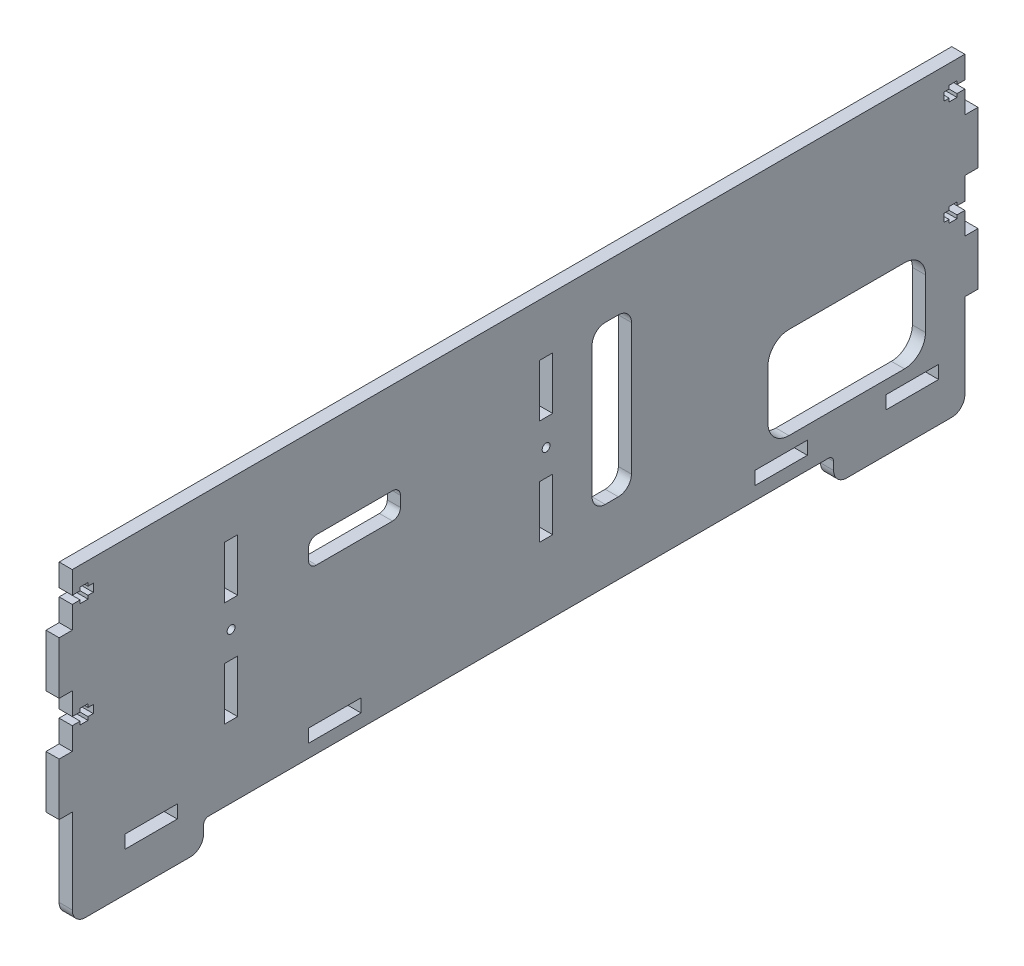
SolidWorks part; units mm, degrees
ref_plane "前视基准面" through (0, 0, 0) normal (0, 0, 1) x (1, 0, 0)
ref_plane "上视基准面" through (0, 0, 0) normal (0, 1, 0) x (1, 0, 0)
ref_plane "右视基准面" through (0, 0, 0) normal (1, 0, 0) x (0, 0, -1)
sketch "草图1" plane through (0, 0, 0) normal (1, 0, 0) x (0, 0, -1)
  line L0 (-75.7709, -36.3237) -> (-75.7709, -33.3237)
  line L1 (-125.7709, 75.9763) -> (214.2291, 75.9763)
  line L2 (-125.7709, 75.9763) -> (-125.7709, 67.4763)
  line L3 (-120.7709, -41.3237) -> (-80.7709, -41.3237)
  line L4 (214.2291, 75.9763) -> (214.2291, 67.4763)
  line L5 (-73.7709, -31.3237) -> (162.2291, -31.3237)
  line L6 (164.2291, -33.3237) -> (164.2291, -36.3237)
  line L7 (-130.7709, 83.5386) -> (-130.7709, -56.3914) construction
  line L8 (219.2291, -54.2304) -> (219.2291, 91.1431) construction
  line L9 (-125.7709, 35.9763) -> (-125.7709, 27.4763)
  line L10 (-130.7709, 55.9763) -> (-125.7709, 55.9763)
  line L11 (-130.7709, 55.9763) -> (-130.7709, 35.9763)
  line L12 (-130.7709, 35.9763) -> (-125.7709, 35.9763)
  line L13 (-125.7709, -4.0237) -> (-125.7709, -36.3237)
  line L14 (-130.7709, 15.9763) -> (-125.7709, 15.9763)
  line L15 (-130.7709, 15.9763) -> (-130.7709, -4.0237)
  line L16 (-130.7709, -4.0237) -> (-125.7709, -4.0237)
  line L17 (214.2291, 35.9763) -> (214.2291, 27.4763)
  line L18 (214.2291, 55.9763) -> (219.2291, 55.9763)
  line L19 (214.2291, -4.0237) -> (214.2291, -36.3237)
  line L20 (214.2291, 35.9763) -> (219.2291, 35.9763)
  line L21 (219.2291, 55.9763) -> (219.2291, 35.9763)
  line L22 (214.2291, 15.9763) -> (219.2291, 15.9763)
  line L23 (169.2291, -41.3237) -> (209.2291, -41.3237)
  line L24 (214.2291, -4.0237) -> (219.2291, -4.0237)
  line L25 (219.2291, 15.9763) -> (219.2291, -4.0237)
  line L26 (-67.7709, 106.6137) -> (-67.7709, -95.6066) construction
  line L27 (57.2291, 100.1396) -> (57.2291, -68.1869) construction
  line L28 (-105.7709, 93.1876) -> (-105.7709, -75.8237) construction
  line L29 (57.2291, 55.9763) -> (52.2291, 55.9763)
  line L30 (57.2291, 55.9763) -> (57.2291, 35.9763)
  line L31 (57.2291, 35.9763) -> (52.2291, 35.9763)
  line L32 (52.2291, 55.9763) -> (52.2291, 35.9763)
  line L33 (57.2291, 15.9763) -> (52.2291, 15.9763)
  line L34 (57.2291, 15.9763) -> (57.2291, -4.0237)
  line L35 (57.2291, -4.0237) -> (52.2291, -4.0237)
  line L36 (52.2291, 15.9763) -> (52.2291, -4.0237)
  line L37 (-67.7709, 55.9763) -> (-62.7709, 55.9763)
  line L38 (-67.7709, 55.9763) -> (-67.7709, 35.9763)
  line L39 (-67.7709, 35.9763) -> (-62.7709, 35.9763)
  line L40 (-62.7709, 55.9763) -> (-62.7709, 35.9763)
  line L41 (-67.7709, 15.9763) -> (-62.7709, 15.9763)
  line L42 (-67.7709, 15.9763) -> (-67.7709, -4.0237)
  line L43 (-67.7709, -4.0237) -> (-62.7709, -4.0237)
  line L44 (-62.7709, 15.9763) -> (-62.7709, -4.0237)
  line L45 (-15.7709, 93.1876) -> (-15.7709, -75.8237) construction
  line L46 (-15.7709, -26.3237) -> (255.6301, -26.3237) construction
  line L47 (-15.7709, -21.3237) -> (-35.7709, -21.3237)
  line L48 (-15.7709, -21.3237) -> (-15.7709, -26.3237)
  line L49 (-15.7709, -26.3237) -> (-35.7709, -26.3237)
  line L50 (-35.7709, -21.3237) -> (-35.7709, -26.3237)
  line L51 (-85.7709, -21.3237) -> (-105.7709, -21.3237)
  line L52 (-85.7709, -21.3237) -> (-85.7709, -26.3237)
  line L53 (-85.7709, -26.3237) -> (-105.7709, -26.3237)
  line L54 (-105.7709, -21.3237) -> (-105.7709, -26.3237)
  line L55 (204.2291, 86.5162) -> (204.2291, -54.2304) construction
  line L56 (214.2291, 67.4763) -> (211.2291, 67.4763)
  line L57 (204.2291, -26.3237) -> (184.2291, -26.3237)
  line L58 (204.2291, -26.3237) -> (204.2291, -21.3237)
  line L59 (204.2291, -21.3237) -> (184.2291, -21.3237)
  line L60 (184.2291, -26.3237) -> (184.2291, -21.3237)
  line L61 (154.2291, -26.3237) -> (134.2291, -26.3237)
  line L62 (154.2291, -26.3237) -> (154.2291, -21.3237)
  line L63 (154.2291, -21.3237) -> (134.2291, -21.3237)
  line L64 (134.2291, -26.3237) -> (134.2291, -21.3237)
  line L65 (191.2291, 18.6763) -> (147.2291, 18.6763)
  line L66 (199.2291, 10.6763) -> (199.2291, -8.3237)
  line L67 (191.2291, -16.3237) -> (147.2291, -16.3237)
  line L68 (139.2291, 10.6763) -> (139.2291, -8.3237)
  line L69 (82.2291, 55.9763) -> (77.2291, 55.9763)
  line L70 (87.2291, 50.9763) -> (87.2291, 0.9763)
  line L71 (82.2291, -4.0237) -> (77.2291, -4.0237)
  line L72 (72.2291, 50.9763) -> (72.2291, 0.9763)
  line L73 (-32.7709, 40.9763) -> (-3.7709, 40.9763)
  line L74 (-35.7709, 37.9763) -> (-35.7709, 33.9763)
  line L75 (-32.7709, 30.9763) -> (-3.7709, 30.9763)
  line L76 (-0.7709, 37.9763) -> (-0.7709, 33.9763)
  line L77 (206.2291, 67.4763) -> (206.2291, 64.4763)
  line L78 (206.2291, 64.4763) -> (208.2291, 64.4763)
  line L79 (211.2291, 64.4763) -> (211.2291, 63.2263)
  line L80 (211.2291, 68.7263) -> (208.2291, 68.7263)
  line L81 (211.2291, 68.7263) -> (211.2291, 67.4763)
  line L82 (211.2291, 63.2263) -> (208.2291, 63.2263)
  line L83 (208.2291, 68.7263) -> (208.2291, 67.4763)
  line L84 (208.2291, 67.4763) -> (206.2291, 67.4763)
  line L85 (208.2291, 64.4763) -> (208.2291, 63.2263)
  line L86 (211.2291, 64.4763) -> (214.2291, 64.4763)
  line L87 (214.2291, 64.4763) -> (214.2291, 55.9763)
  line L88 (-125.7709, 67.4763) -> (-122.7709, 67.4763)
  line L89 (-122.7709, 67.4763) -> (-122.7709, 68.7263)
  line L90 (-122.7709, 68.7263) -> (-119.7709, 68.7263)
  line L91 (-119.7709, 68.7263) -> (-119.7709, 67.4763)
  line L92 (-119.7709, 67.4763) -> (-117.7709, 67.4763)
  line L93 (-117.7709, 67.4763) -> (-117.7709, 64.4763)
  line L94 (-117.7709, 64.4763) -> (-119.7709, 64.4763)
  line L95 (-119.7709, 64.4763) -> (-119.7709, 63.2263)
  line L96 (-119.7709, 63.2263) -> (-122.7709, 63.2263)
  line L97 (-122.7709, 63.2263) -> (-122.7709, 64.4763)
  line L98 (-122.7709, 64.4763) -> (-125.7709, 64.4763)
  line L99 (214.2291, 27.4763) -> (211.2291, 27.4763)
  line L100 (206.2291, 27.4763) -> (206.2291, 24.4763)
  line L101 (206.2291, 24.4763) -> (208.2291, 24.4763)
  line L102 (211.2291, 24.4763) -> (211.2291, 23.2263)
  line L103 (211.2291, 28.7263) -> (208.2291, 28.7263)
  line L104 (211.2291, 28.7263) -> (211.2291, 27.4763)
  line L105 (211.2291, 23.2263) -> (208.2291, 23.2263)
  line L106 (208.2291, 28.7263) -> (208.2291, 27.4763)
  line L107 (208.2291, 27.4763) -> (206.2291, 27.4763)
  line L108 (208.2291, 24.4763) -> (208.2291, 23.2263)
  line L109 (211.2291, 24.4763) -> (214.2291, 24.4763)
  line L110 (214.2291, 24.4763) -> (214.2291, 15.9763)
  line L111 (-125.7709, 27.4763) -> (-122.7709, 27.4763)
  line L112 (-122.7709, 27.4763) -> (-122.7709, 28.7263)
  line L113 (-122.7709, 28.7263) -> (-119.7709, 28.7263)
  line L114 (-119.7709, 28.7263) -> (-119.7709, 27.4763)
  line L115 (-119.7709, 27.4763) -> (-117.7709, 27.4763)
  line L116 (-117.7709, 27.4763) -> (-117.7709, 24.4763)
  line L117 (-117.7709, 24.4763) -> (-119.7709, 24.4763)
  line L118 (-119.7709, 24.4763) -> (-119.7709, 23.2263)
  line L119 (-119.7709, 23.2263) -> (-122.7709, 23.2263)
  line L120 (-122.7709, 23.2263) -> (-122.7709, 24.4763)
  line L121 (-122.7709, 24.4763) -> (-125.7709, 24.4763)
  line L122 (-125.7709, 64.4763) -> (-125.7709, 55.9763)
  line L123 (-125.7709, 24.4763) -> (-125.7709, 15.9763)
  arc A0 (209.2291, -41.3237) -> (214.2291, -36.3237) centre (209.2291, -36.3237) ccw
  arc A1 (164.2291, -36.3237) -> (169.2291, -41.3237) centre (169.2291, -36.3237) ccw
  arc A2 (-75.7709, -36.3237) -> (-80.7709, -41.3237) centre (-80.7709, -36.3237) cw
  arc A3 (-125.7709, -36.3237) -> (-120.7709, -41.3237) centre (-120.7709, -36.3237) ccw
  arc A4 (162.2291, -31.3237) -> (164.2291, -33.3237) centre (162.2291, -33.3237) cw
  arc A5 (-75.7709, -33.3237) -> (-73.7709, -31.3237) centre (-73.7709, -33.3237) cw
  arc A6 (147.2291, 18.6763) -> (139.2291, 10.6763) centre (147.2291, 10.6763) ccw
  arc A7 (147.2291, -16.3237) -> (139.2291, -8.3237) centre (147.2291, -8.3237) cw
  arc A8 (199.2291, -8.3237) -> (191.2291, -16.3237) centre (191.2291, -8.3237) cw
  arc A9 (191.2291, 18.6763) -> (199.2291, 10.6763) centre (191.2291, 10.6763) cw
  arc A10 (87.2291, 0.9763) -> (82.2291, -4.0237) centre (82.2291, 0.9763) cw
  arc A11 (77.2291, -4.0237) -> (72.2291, 0.9763) centre (77.2291, 0.9763) cw
  arc A12 (77.2291, 55.9763) -> (72.2291, 50.9763) centre (77.2291, 50.9763) ccw
  arc A13 (82.2291, 55.9763) -> (87.2291, 50.9763) centre (82.2291, 50.9763) cw
  arc A14 (-32.7709, 40.9763) -> (-35.7709, 37.9763) centre (-32.7709, 37.9763) ccw
  arc A15 (-35.7709, 33.9763) -> (-32.7709, 30.9763) centre (-32.7709, 33.9763) ccw
  arc A16 (-3.7709, 30.9763) -> (-0.7709, 33.9763) centre (-3.7709, 33.9763) ccw
  arc A17 (-3.7709, 40.9763) -> (-0.7709, 37.9763) centre (-3.7709, 37.9763) cw
  circle A18 centre (54.7291, 25.9763) radius 1.5
  circle A19 centre (-65.2709, 25.9763) radius 1.5
  point P30 (214.2291, -41.3237)
  point P33 (164.2291, -41.3237)
  point P38 (-125.7709, -41.3237)
  point P63 (54.7291, 15.9763)
  point P76 (-15.7709, -23.8237)
  point P94 (139.2291, 18.6763)
  point P97 (139.2291, -16.3237)
  point P102 (199.2291, 18.6763)
  point P109 (87.2291, -4.0237)
  point P114 (72.2291, 55.9763)
  point P117 (87.2291, 55.9763)
  dimension "D16" = 5
  dimension "D17" = 2
  dimension "D50" = 8
  dimension "D54" = 5
  dimension "D55" = 3
  dimension "D72" = 2.5
  dimension "D1" = 340
  dimension "D2" = 117.3
  dimension "D3" = 5
  dimension "D4" = 5
  dimension "D5" = 20
  dimension "D6" = 20
  dimension "D7" = 20
  dimension "D8" = 20
  dimension "D9" = 20
  dimension "D10" = 20
  dimension "D11" = 20
  dimension "D12" = 20
  dimension "D13" = 50
  dimension "D14" = 50
  dimension "D15" = 10
  dimension "D18" = 58
  dimension "D19" = 125
  dimension "D20" = 5
  dimension "D21" = 5
  dimension "D22" = 5
  dimension "D23" = 5
  dimension "D24" = 20
  dimension "D25" = 20
  dimension "D26" = 20
  dimension "D27" = 20
  dimension "D28" = 20
  dimension "D29" = 20
  dimension "D30" = 20
  dimension "D31" = 20
  dimension "D32" = 20
  dimension "D33" = 90
  dimension "D34" = 20
  dimension "D35" = 20
  dimension "D36" = 5
  dimension "D37" = 5
  dimension "D38" = 0
  dimension "D39" = 0
  dimension "D40" = 5
  dimension "D41" = 5
  dimension "D42" = 10
  dimension "D43" = 30
  dimension "D44" = 20
  dimension "D45" = 20
  dimension "D46" = 60
  dimension "D47" = 35
  dimension "D48" = 5
  dimension "D49" = 5
  dimension "D51" = 15
  dimension "D52" = 60
  dimension "D53" = 15
  dimension "D56" = 35
  dimension "D57" = 10
  dimension "D58" = 35
  dimension "D59" = 5.5
  dimension "D60" = 1.25
  dimension "D61" = 3
  dimension "D62" = 8
  dimension "D63" = 3
  dimension "D64" = 8.5
  dimension "D65" = 5.5
  dimension "D66" = 3
  dimension "D67" = 8.5
  dimension "D68" = 3
  dimension "D69" = 5.5
  dimension "D70" = 3
  dimension "D71" = 8.5
  dimension "D73" = 10
  dimension "D74" = 5.5
  dimension "D75" = 1.25
  dimension "D76" = 8
  dimension "D77" = 3
  dimension "D78" = 1.25
  dimension "D79" = 1.25
  dimension "D80" = 3
  dimension "D81" = 3
  dimension "D82" = 3
  dimension "D83" = 3
  dimension "D84" = 2.5
  dimension "D85" = 8.5
  dimension "D86" = 10
extrude "凸台-拉伸1" add sketch "草图1" along normal blind 5
